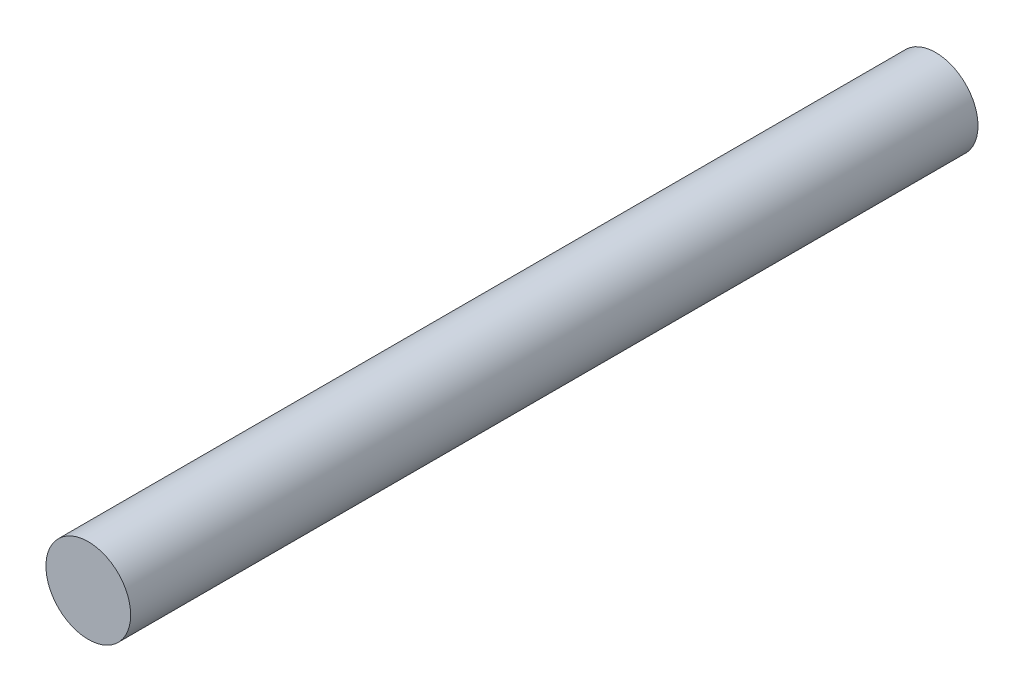
SolidWorks part; units mm, degrees
ref_plane "Front Plane" through (0, 0, 0) normal (0, 0, 1) x (1, 0, 0)
ref_plane "Top Plane" through (0, 0, 0) normal (0, 1, 0) x (1, 0, 0)
ref_plane "Right Plane" through (0, 0, 0) normal (1, 0, 0) x (0, 0, -1)
sketch "Sketch1" plane through (0, 0, 0) normal (0, 0, 1) x (1, 0, 0)
  circle A0 centre (0, 0) radius 5
  dimension "D1" = 10
extrude "Boss-Extrude1" add sketch "Sketch1" along normal blind 100
